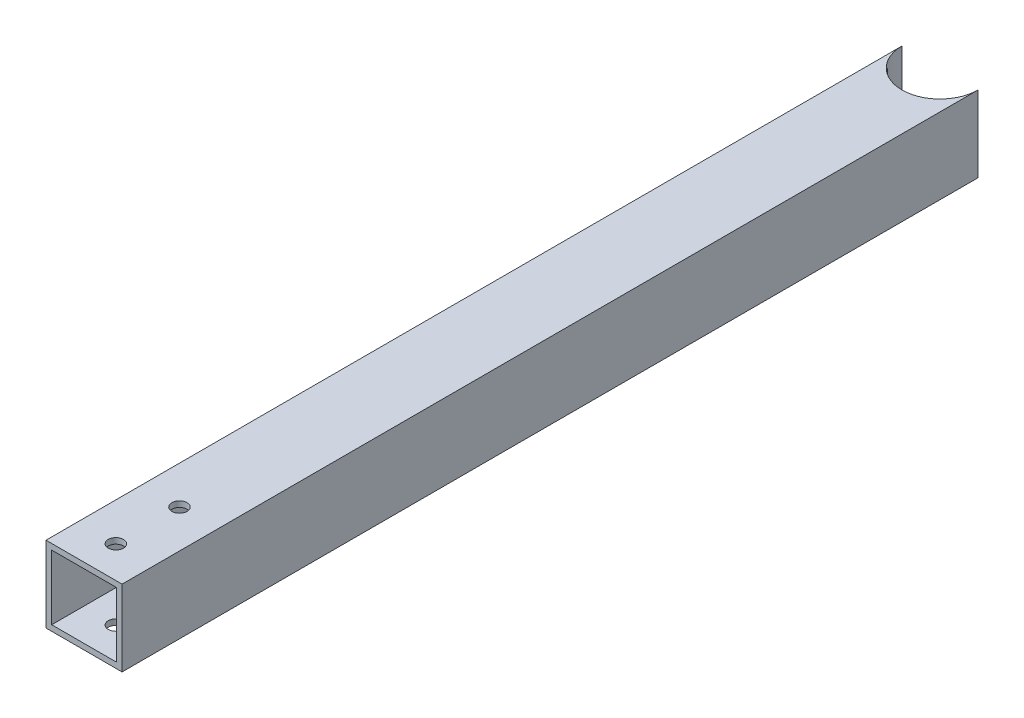
SolidWorks part; units mm, degrees
ref_plane "Front Plane" through (0, 0, 0) normal (0, 0, 1) x (1, 0, 0)
ref_plane "Top Plane" through (0, 0, 0) normal (0, 1, 0) x (1, 0, 0)
ref_plane "Right Plane" through (0, 0, 0) normal (1, 0, 0) x (0, 0, -1)
sketch "Sketch1" plane through (0, 0, 0) normal (0, 0, 1) x (1, 0, 0)
  line L0 (3, 3) -> (3, 37)
  line L1 (0, 0) -> (40, 0)
  line L2 (0, 0) -> (0, 40)
  line L3 (0, 40) -> (40, 40)
  line L4 (40, 0) -> (40, 40)
  line L5 (3, 37) -> (37, 37)
  line L6 (37, 3) -> (37, 37)
  line L7 (3, 3) -> (37, 3)
  dimension "D1" = 40
  dimension "D2" = 40
  dimension "D3" = 3
extrude "Boss-Extrude1" add sketch "Sketch1" along normal blind 450 contours L3 L4 L1 L2
sketch "Sketch2" plane through (0, 40, 0) normal (0, 1, 0) x (1, 0, 0)
  line L0 (30, -450) -> (30, -383.0924)
  line L1 (30, -383.0924) -> (10, -383.0924)
  line L2 (10, -383.0924) -> (10, -450)
  line L3 (10, -450) -> (30, -450)
  line L4 (40, 0) -> (0, 0) construction
  circle A0 centre (20, -433.2731) radius 4
  circle A1 centre (20, -399.8193) radius 4
  circle A2 centre (20, 0) radius 20
extrude "Cut-Extrude1" cut sketch "Sketch2" against normal blind 600 contours A1 | A0 | A2
sketch "Sketch3" plane through (0, 0, 0) normal (-1, 0, 0) x (0, 0, 1)
  line L0 (200, 40) -> (200, 23.6732)
  line L1 (450, 40) -> (0, 40) construction
  line L2 (0, 40) -> (0, 0) construction
  dimension "D1" = 200
